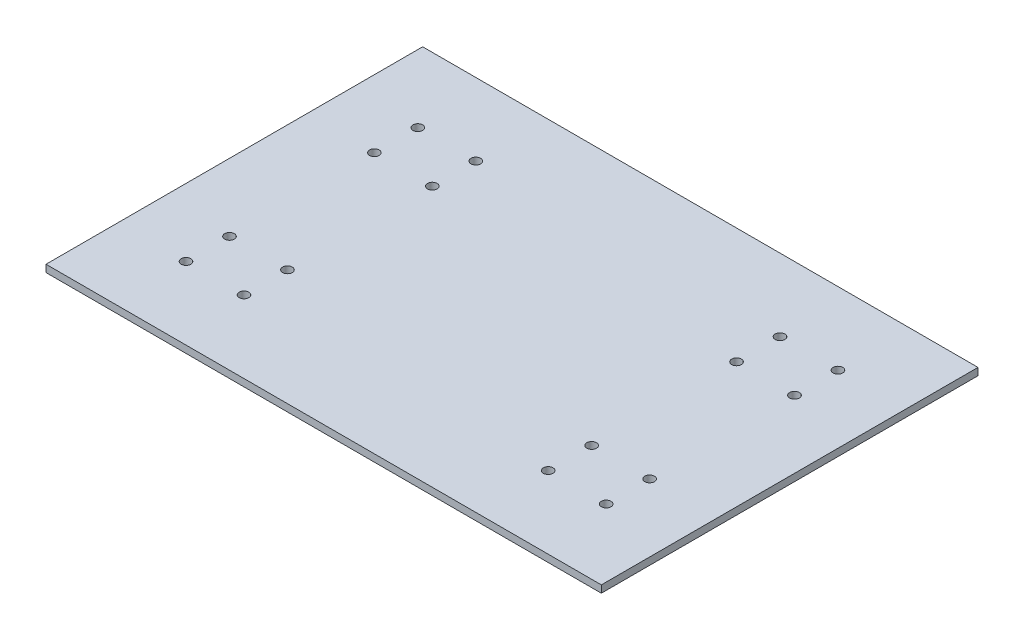
SolidWorks part; units mm, degrees
ref_plane "Front Plane" through (0, 0, 0) normal (0, 0, 1) x (1, 0, 0)
ref_plane "Top Plane" through (0, 0, 0) normal (0, 1, 0) x (1, 0, 0)
ref_plane "Right Plane" through (0, 0, 0) normal (1, 0, 0) x (0, 0, -1)
sketch "Sketch1" plane through (0, 0, 0) normal (0, 1, 0) x (1, 0, 0)
  line L1 (-115, -78) -> (115, -78)
  line L2 (-115, -78) -> (-115, 78)
  line L3 (-115, 78) -> (115, 78)
  line L4 (115, -78) -> (115, 78)
  line L5 (-115, -78) -> (115, 78) construction
  line L6 (-115, 78) -> (115, -78) construction
  point P0 (0, 0)
  dimension "D1" = 156
  dimension "D2" = 230
extrude "Boss-Extrude1" add sketch "Sketch1" along normal blind 3
sketch "Sketch2" plane through (0, 3, 0) normal (0, 1, 0) x (1, 0, 0)
  line L0 (0, -1000) -> (0, 49000) construction
  line L1 (-1000, 0) -> (49000, 0) construction
  line L2 (75, -1000) -> (75, 49000) construction
  line L3 (-75, -1000) -> (-75, 49000) construction
  line L4 (-1000, -39) -> (49000, -39) construction
  line L5 (-1000, 39) -> (49000, 39) construction
  line L6 (-63, 30) -> (-87, 48) construction
  line L7 (63, 48) -> (87, 48) construction
  line L8 (63, 48) -> (63, 30) construction
  line L9 (63, 30) -> (87, 30) construction
  line L10 (87, 48) -> (87, 30) construction
  line L11 (63, 48) -> (87, 30) construction
  line L12 (63, 30) -> (87, 48) construction
  line L13 (-63, 48) -> (-87, 30) construction
  line L14 (-87, 48) -> (-87, 30) construction
  line L15 (-63, 30) -> (-87, 30) construction
  line L16 (-63, 48) -> (-63, 30) construction
  line L17 (-63, 48) -> (-87, 48) construction
  line L18 (-63, -48) -> (-87, -48) construction
  line L19 (-63, -48) -> (-63, -30) construction
  line L20 (-63, -30) -> (-87, -30) construction
  line L21 (-87, -48) -> (-87, -30) construction
  line L22 (-63, -48) -> (-87, -30) construction
  line L23 (63, -30) -> (87, -48) construction
  line L24 (63, -48) -> (87, -30) construction
  line L25 (87, -48) -> (87, -30) construction
  line L26 (63, -30) -> (87, -30) construction
  line L27 (63, -48) -> (63, -30) construction
  line L28 (63, -48) -> (87, -48) construction
  line L29 (-63, -30) -> (-87, -48) construction
  circle A0 centre (63, 48) radius 2
  circle A1 centre (87, 48) radius 2
  circle A2 centre (87, 30) radius 2
  circle A3 centre (63, 30) radius 2
  circle A4 centre (-63, 30) radius 2
  circle A5 centre (-87, 30) radius 2
  circle A6 centre (-87, 48) radius 2
  circle A7 centre (-63, 48) radius 2
  circle A8 centre (-63, -48) radius 2
  circle A9 centre (-87, -48) radius 2
  circle A10 centre (-87, -30) radius 2
  circle A11 centre (-63, -30) radius 2
  circle A12 centre (63, -30) radius 2
  circle A13 centre (87, -30) radius 2
  circle A14 centre (87, -48) radius 2
  circle A15 centre (63, -48) radius 2
  point P13 (75, 39)
  point P30 (-75, 39)
  point P47 (-75, -39)
  point P48 (75, -39)
  dimension "D7" = 4
  dimension "D5" = 18
  dimension "D6" = 24
  dimension "D1" = 75
  dimension "D2" = 75
  dimension "D3" = 39
  dimension "D4" = 39
extrude "Cut-Extrude1" cut sketch "Sketch2" against normal through all
